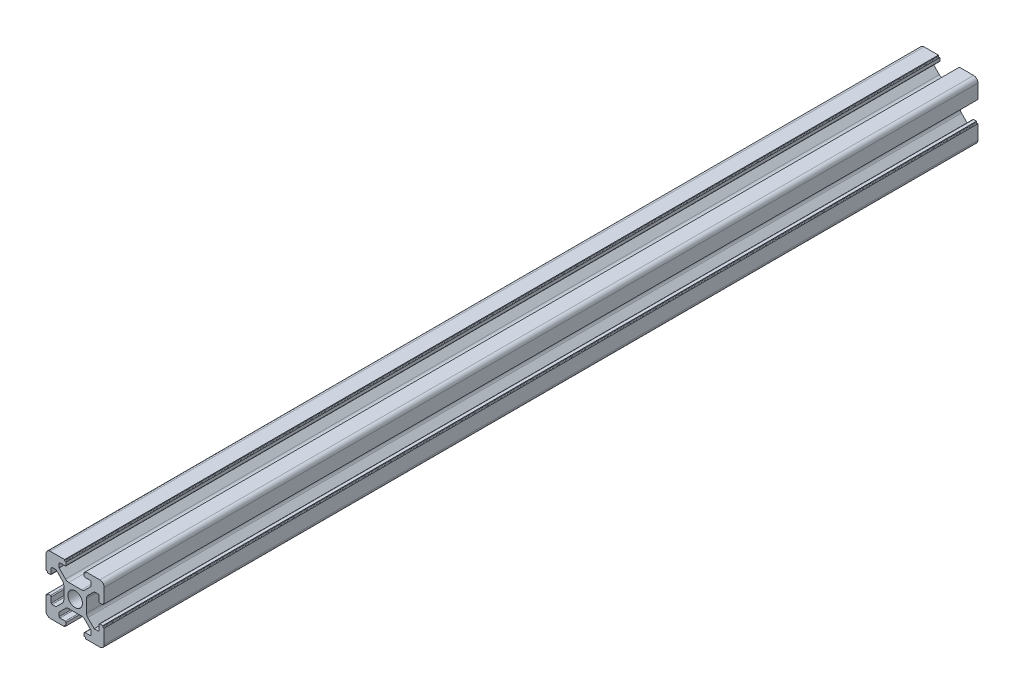
SolidWorks part; units mm, degrees
ref_plane "前视基准面" through (0, 0, 0) normal (0, 0, 1) x (1, 0, 0)
ref_plane "上视基准面" through (0, 0, 0) normal (0, 1, 0) x (1, 0, 0)
ref_plane "右视基准面" through (0, 0, 0) normal (1, 0, 0) x (0, 0, -1)
sketch "草图1" plane through (0, 0, 0) normal (0, 0, 1) x (1, 0, 0)
  line L0 (4.216, 3.2442) -> (6.4367, 5.4649)
  line L1 (6.4367, 5.4649) -> (7.7767, 5.4649)
  line L2 (8.0767, 5.1649) -> (8.0767, 3.3649)
  line L3 (8.3767, 3.0649) -> (9.3767, 3.0649)
  line L4 (9.3767, 3.0649) -> (9.3767, 3.3649)
  line L5 (9.5767, 3.5649) -> (9.8767, 3.5649)
  line L6 (9.8767, 3.5649) -> (9.8767, 8.4649)
  line L7 (8.3767, 9.9649) -> (3.4767, 9.9649)
  line L8 (3.4767, 9.9649) -> (3.4767, 9.6649)
  line L9 (3.2767, 9.4649) -> (2.9767, 9.4649)
  line L10 (2.9767, 9.4649) -> (2.9767, 8.4649)
  line L11 (3.2767, 8.1649) -> (5.0767, 8.1649)
  line L12 (5.3767, 7.8649) -> (5.3767, 6.5249)
  line L13 (5.3767, 6.5249) -> (3.156, 4.3042)
  line L14 (2.0953, 3.8649) -> (-2.342, 3.8649)
  line L15 (-3.4027, 4.3042) -> (-5.6233, 6.5249)
  line L16 (-5.6233, 6.5249) -> (-5.6233, 7.8649)
  line L17 (-5.3233, 8.1649) -> (-3.5233, 8.1649)
  line L18 (-3.2233, 8.4649) -> (-3.2233, 9.4649)
  line L19 (-3.2233, 9.4649) -> (-3.5233, 9.4649)
  line L20 (-3.7233, 9.6649) -> (-3.7233, 9.9649)
  line L21 (-3.7233, 9.9649) -> (-8.6233, 9.9649)
  line L22 (-10.1233, 8.4649) -> (-10.1233, 3.5649)
  line L23 (-10.1233, 3.5649) -> (-9.8233, 3.5649)
  line L24 (-9.6233, 3.3649) -> (-9.6233, 3.0649)
  line L25 (-9.6233, 3.0649) -> (-8.6233, 3.0649)
  line L26 (-8.3233, 3.3649) -> (-8.3233, 5.1649)
  line L27 (-8.0233, 5.4649) -> (-6.6833, 5.4649)
  line L28 (-6.6833, 5.4649) -> (-4.4627, 3.2442)
  line L29 (-4.0233, 2.1836) -> (-4.0233, -2.2538)
  line L30 (-4.4627, -3.3144) -> (-6.6833, -5.5351)
  line L31 (-6.6833, -5.5351) -> (-8.0233, -5.5351)
  line L32 (-8.3233, -5.2351) -> (-8.3233, -3.4351)
  line L33 (-8.6233, -3.1351) -> (-9.6233, -3.1351)
  line L34 (-9.6233, -3.1351) -> (-9.6233, -3.4351)
  line L35 (-9.8233, -3.6351) -> (-10.1233, -3.6351)
  line L36 (-10.1233, -3.6351) -> (-10.1233, -8.5351)
  line L37 (-8.6233, -10.0351) -> (-3.7233, -10.0351)
  line L38 (-3.7233, -10.0351) -> (-3.7233, -9.7351)
  line L39 (-3.5233, -9.5351) -> (-3.2233, -9.5351)
  line L40 (-3.2233, -9.5351) -> (-3.2233, -8.5351)
  line L41 (-3.5233, -8.2351) -> (-5.3233, -8.2351)
  line L42 (-5.6233, -7.9351) -> (-5.6233, -6.5951)
  line L43 (-5.6233, -6.5951) -> (-3.4027, -4.3744)
  line L44 (-2.342, -3.9351) -> (2.0953, -3.9351)
  line L45 (3.156, -4.3744) -> (5.3767, -6.5951)
  line L46 (5.3767, -6.5951) -> (5.3767, -7.9351)
  line L47 (5.0767, -8.2351) -> (3.2767, -8.2351)
  line L48 (2.9767, -8.5351) -> (2.9767, -9.5351)
  line L49 (2.9767, -9.5351) -> (3.2767, -9.5351)
  line L50 (3.4767, -9.7351) -> (3.4767, -10.0351)
  line L51 (3.4767, -10.0351) -> (8.3767, -10.0351)
  line L52 (9.8767, -8.5351) -> (9.8767, -3.6351)
  line L53 (9.8767, -3.6351) -> (9.5767, -3.6351)
  line L54 (9.3767, -3.4351) -> (9.3767, -3.1351)
  line L55 (9.3767, -3.1351) -> (8.3767, -3.1351)
  line L56 (8.0767, -3.4351) -> (8.0767, -5.2351)
  line L57 (7.7767, -5.5351) -> (6.4367, -5.5351)
  line L58 (6.4367, -5.5351) -> (4.216, -3.3144)
  line L59 (3.7767, -2.2538) -> (3.7767, 2.1836)
  circle A0 centre (-0.1233, -0.0351) radius 2.5
  arc A1 (8.0767, 5.1649) -> (7.7767, 5.4649) centre (7.7767, 5.1649) ccw
  arc A2 (8.0767, 3.3649) -> (8.3767, 3.0649) centre (8.3767, 3.3649) ccw
  arc A3 (9.5767, 3.5649) -> (9.3767, 3.3649) centre (9.5767, 3.3649) ccw
  arc A4 (9.8767, 8.4649) -> (8.3767, 9.9649) centre (8.3767, 8.4649) ccw
  arc A5 (3.2767, 9.4649) -> (3.4767, 9.6649) centre (3.2767, 9.6649) ccw
  arc A6 (2.9767, 8.4649) -> (3.2767, 8.1649) centre (3.2767, 8.4649) ccw
  arc A7 (5.3767, 7.8649) -> (5.0767, 8.1649) centre (5.0767, 7.8649) ccw
  arc A8 (2.0953, 3.8649) -> (3.156, 4.3042) centre (2.0953, 5.3649) ccw
  arc A9 (-3.4027, 4.3042) -> (-2.342, 3.8649) centre (-2.342, 5.3649) ccw
  arc A10 (-5.3233, 8.1649) -> (-5.6233, 7.8649) centre (-5.3233, 7.8649) ccw
  arc A11 (-3.5233, 8.1649) -> (-3.2233, 8.4649) centre (-3.5233, 8.4649) ccw
  arc A12 (-3.7233, 9.6649) -> (-3.5233, 9.4649) centre (-3.5233, 9.6649) ccw
  arc A13 (-8.6233, 9.9649) -> (-10.1233, 8.4649) centre (-8.6233, 8.4649) ccw
  arc A14 (-9.6233, 3.3649) -> (-9.8233, 3.5649) centre (-9.8233, 3.3649) ccw
  arc A15 (-8.6233, 3.0649) -> (-8.3233, 3.3649) centre (-8.6233, 3.3649) ccw
  arc A16 (-8.0233, 5.4649) -> (-8.3233, 5.1649) centre (-8.0233, 5.1649) ccw
  arc A17 (-4.0233, 2.1836) -> (-4.4627, 3.2442) centre (-5.5233, 2.1836) ccw
  arc A18 (-4.4627, -3.3144) -> (-4.0233, -2.2538) centre (-5.5233, -2.2538) ccw
  arc A19 (-8.3233, -5.2351) -> (-8.0233, -5.5351) centre (-8.0233, -5.2351) ccw
  arc A20 (-8.3233, -3.4351) -> (-8.6233, -3.1351) centre (-8.6233, -3.4351) ccw
  arc A21 (-9.8233, -3.6351) -> (-9.6233, -3.4351) centre (-9.8233, -3.4351) ccw
  arc A22 (-10.1233, -8.5351) -> (-8.6233, -10.0351) centre (-8.6233, -8.5351) ccw
  arc A23 (-3.5233, -9.5351) -> (-3.7233, -9.7351) centre (-3.5233, -9.7351) ccw
  arc A24 (-3.2233, -8.5351) -> (-3.5233, -8.2351) centre (-3.5233, -8.5351) ccw
  arc A25 (-5.6233, -7.9351) -> (-5.3233, -8.2351) centre (-5.3233, -7.9351) ccw
  arc A26 (-2.342, -3.9351) -> (-3.4027, -4.3744) centre (-2.342, -5.4351) ccw
  arc A27 (3.156, -4.3744) -> (2.0953, -3.9351) centre (2.0953, -5.4351) ccw
  arc A28 (5.0767, -8.2351) -> (5.3767, -7.9351) centre (5.0767, -7.9351) ccw
  arc A29 (3.2767, -8.2351) -> (2.9767, -8.5351) centre (3.2767, -8.5351) ccw
  arc A30 (3.4767, -9.7351) -> (3.2767, -9.5351) centre (3.2767, -9.7351) ccw
  arc A31 (8.3767, -10.0351) -> (9.8767, -8.5351) centre (8.3767, -8.5351) ccw
  arc A32 (9.3767, -3.4351) -> (9.5767, -3.6351) centre (9.5767, -3.4351) ccw
  arc A33 (8.3767, -3.1351) -> (8.0767, -3.4351) centre (8.3767, -3.4351) ccw
  arc A34 (7.7767, -5.5351) -> (8.0767, -5.2351) centre (7.7767, -5.2351) ccw
  arc A35 (3.7767, -2.2538) -> (4.216, -3.3144) centre (5.2767, -2.2538) ccw
  arc A36 (4.216, 3.2442) -> (3.7767, 2.1836) centre (5.2767, 2.1836) ccw
extrude "凸台-拉伸1" add sketch "草图1" along normal blind 300
